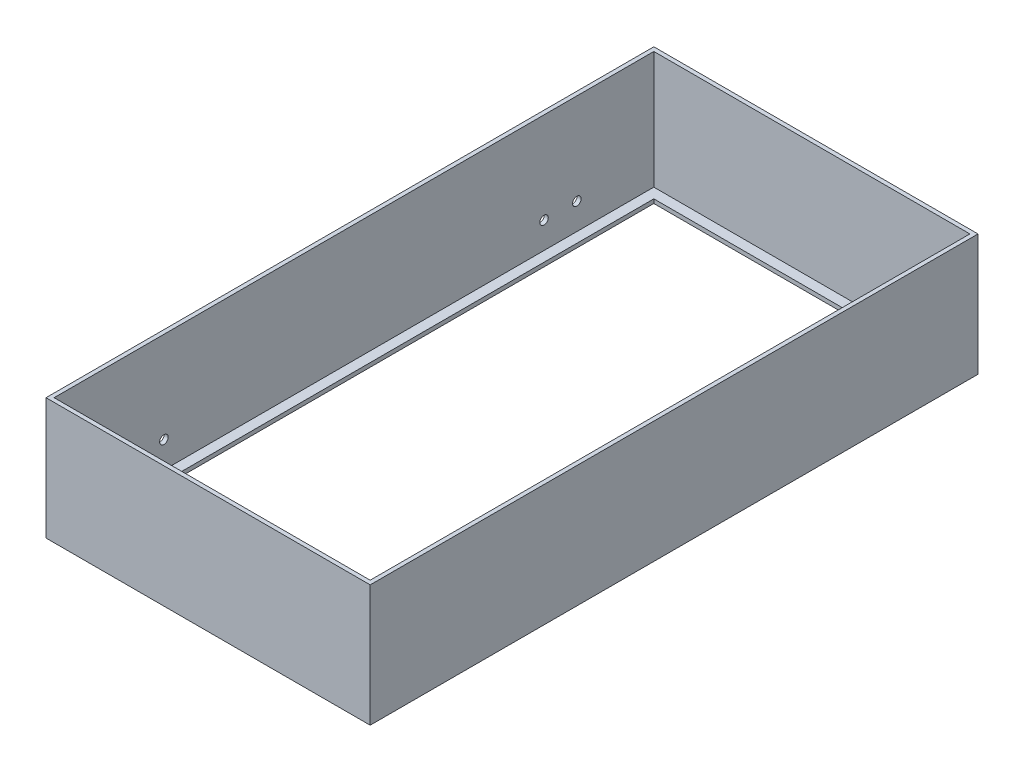
SolidWorks part; units mm, degrees
ref_plane "Front Plane" through (0, 0, 0) normal (0, 0, 1) x (1, 0, 0)
ref_plane "Top Plane" through (0, 0, 0) normal (0, 1, 0) x (1, 0, 0)
ref_plane "Right Plane" through (0, 0, 0) normal (1, 0, 0) x (0, 0, -1)
sketch "Sketch2" plane through (0, 0, 0) normal (0, 0, 1) x (1, 0, 0)
  line L2 (203.2, 0) -> (203.2, 76.2)
  line L3 (203.2, 76.2) -> (0, 76.2)
  line L4 (0, 76.2) -> (0, 0)
  line L5 (203.2, 0) -> (0, 0)
  dimension "D1" = 203.2
  dimension "D2" = 76.2
extrude "Boss-Extrude1" add sketch "Sketch2" along normal blind 381
sketch "Sketch3" plane through (0, 76.2, 0) normal (0, 1, 0) x (1, 0, 0)
  line L8 (200.66, -2.54) -> (2.54, -2.54)
  line L9 (2.54, -2.54) -> (2.54, -378.46)
  line L10 (2.54, -378.46) -> (200.66, -378.46)
  line L11 (200.66, -378.46) -> (200.66, -2.54)
  line L12 (200.66, -2.54) -> (2.54, -2.54)
  line L13 (2.54, -2.54) -> (2.54, -378.46)
  line L14 (2.54, -378.46) -> (200.66, -378.46)
  line L15 (200.66, -378.46) -> (200.66, -2.54)
  dimension "D1" = 2.54
extrude "Cut-Extrude1" cut sketch "Sketch3" against normal through all
sketch "Sketch4" plane through (0, 0, 0) normal (0, 1, 0) x (1, 0, 0)
  line L11 (2.54, -2.54) -> (200.66, -2.54)
  line L12 (2.54, -2.54) -> (2.54, -378.46)
  line L13 (2.54, -378.46) -> (200.66, -378.46)
  line L14 (8.89, -372.11) -> (194.31, -372.11)
  line L15 (194.31, -372.11) -> (194.31, -8.89)
  line L16 (8.89, -8.89) -> (8.89, -372.11)
  line L17 (194.31, -8.89) -> (8.89, -8.89)
  line L18 (8.89, -372.11) -> (194.31, -372.11)
  line L19 (194.31, -372.11) -> (194.31, -8.89)
  line L20 (8.89, -8.89) -> (8.89, -372.11)
  line L21 (194.31, -8.89) -> (8.89, -8.89)
  line L22 (200.66, -2.54) -> (200.66, -378.46)
  dimension "D1" = 6.35
extrude "Boss-Extrude2" add sketch "Sketch4" along normal blind 2.54
sketch "Sketch5" plane through (0, 0, 0) normal (-1, 0, 0) x (0, 0, 1)
  line L0 (381, 0) -> (0, 0) construction
  line L1 (381, 76.2) -> (381, 0) construction
  circle A0 centre (309.626, 19.05) radius 2.667
  circle A1 centre (330.2, 19.05) radius 2.667
  dimension "D1" = 5.334
  dimension "D2" = 20.574
  dimension "D3" = 19.05
  dimension "D4" = 50.8
extrude "Cut-Extrude2" cut sketch "Sketch5" against normal blind 2.54
ref_plane "Plane1" through (0, 0, 190.5) normal (0, 0, -1) x (-1, 0, 0)
mirror "Mirror1" about plane through (0, 0, 190.5) normal (0, 0, -1) of "Cut-Extrude2"
